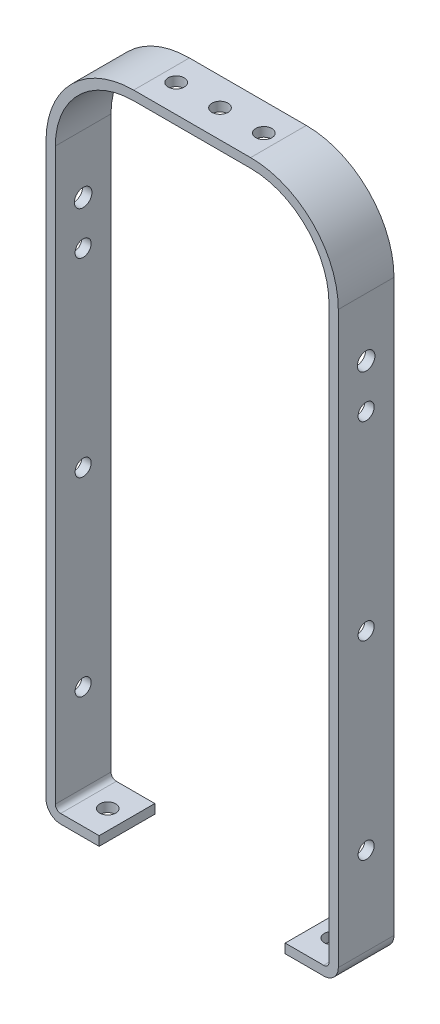
SolidWorks part; units mm, degrees
ref_plane "Front Plane" through (0, 0, 0) normal (0, 0, 1) x (1, 0, 0)
ref_plane "Top Plane" through (0, 0, 0) normal (0, 1, 0) x (1, 0, 0)
ref_plane "Right Plane" through (0, 0, 0) normal (1, 0, 0) x (0, 0, -1)
sketch "Sketch1" plane through (0, 0, 0) normal (0, 0, 1) x (1, 0, 0)
  line L0 (50, 45) -> (50, 240)
  line L1 (0, 0) -> (0, 109.6692) construction
  line L2 (46.825, 240) -> (46.825, 45)
  line L3 (-45, 40) -> (-31.825, 40)
  line L4 (20, 270) -> (-20, 270)
  line L5 (-45, 43.175) -> (-31.825, 43.175)
  line L6 (-20, 266.825) -> (20, 266.825)
  line L7 (-31.825, 43.175) -> (-31.825, 40)
  line L8 (-46.825, 240) -> (-46.825, 45)
  line L9 (-50, 45) -> (-50, 240)
  line L10 (31.825, 43.175) -> (31.825, 40)
  line L11 (45, 43.175) -> (31.825, 43.175)
  line L12 (45, 40) -> (31.825, 40)
  arc A0 (50, 240) -> (20, 270) centre (20, 240) ccw
  arc A1 (20, 266.825) -> (46.825, 240) centre (20, 240) cw
  arc A2 (-20, 266.825) -> (-46.825, 240) centre (-20, 240) ccw
  arc A3 (-50, 240) -> (-20, 270) centre (-20, 240) cw
  arc A4 (-50, 45) -> (-45, 40) centre (-45, 45) ccw
  arc A5 (-46.825, 45) -> (-45, 43.175) centre (-45, 45) ccw
  arc A6 (46.825, 45) -> (45, 43.175) centre (45, 45) cw
  arc A7 (50, 45) -> (45, 40) centre (45, 45) cw
  dimension "D4" = 30
  dimension "D5" = 45
  dimension "D6" = 3.175
  dimension "D7" = 5
  dimension "D1" = 270
  dimension "D2" = 46.825
  dimension "D3" = 40
  dimension "D8" = 15
extrude "Boss-Extrude1" add sketch "Sketch1" along normal mid plane 19.05
sketch "Sketch12" plane through (0, 270, 0) normal (0, 1, 0) x (1, 0, 0)
  line L0 (-20, -9.525) -> (-20, 9.525) construction
  line L1 (20, -9.525) -> (20, 9.525) construction
  circle A0 centre (0, 0) radius 2.75
  circle A1 centre (-15, 0) radius 2.75
  circle A2 centre (15, 0) radius 2.75
  dimension "D1" = 5.5
  dimension "D2" = 5
  dimension "D3" = 5
extrude "Cut-Extrude2" cut sketch "Sketch12" against normal through all
sketch "Sketch13" plane through (50, 0, 0) normal (1, 0, 0) x (0, 0, -1)
  line L0 (0, 0) -> (0, 240) construction
  line L1 (-9.525, 240) -> (9.525, 240) construction
  circle A0 centre (0, 205) radius 2.75
  circle A1 centre (0, 140) radius 2.75
  circle A2 centre (0, 75) radius 2.75
  dimension "D1" = 5.5
  dimension "D4" = 65
  dimension "D3" = 3
extrude "Cut-Extrude3" cut sketch "Sketch13" against normal through all both and the other way through all
sketch "Sketch16" plane through (0, 40, 0) normal (0, -1, 0) x (-1, 0, 0)
  line L0 (38.4125, -9.525) -> (38.4125, 9.525) construction
  line L1 (45, -9.525) -> (31.825, -9.525) construction
  line L2 (45, 9.525) -> (31.825, 9.525) construction
  line L3 (38.4125, 9.525) -> (31.825, 0) construction
  line L4 (31.825, -9.525) -> (31.825, 9.525) construction
  line L5 (31.825, 0) -> (45, 0) construction
  line L6 (45, -9.525) -> (45, 9.525) construction
  line L7 (0, 0) -> (0, -9.525) construction
  line L8 (20, -9.525) -> (-20, -9.525) construction
  circle A0 centre (38.4125, 0) radius 2.75
  circle A1 centre (-38.4125, 0) radius 2.75
  dimension "D1" = 5.5
extrude "Cut-Extrude6" cut sketch "Sketch16" against normal up to next
sketch "Sketch17" plane through (50, 0, 0) normal (1, 0, 0) x (0, 0, -1)
  line L0 (-9.525, 240) -> (9.525, 240) construction
  circle A0 centre (0, 220) radius 3
  point P4 (-2.2021, 225)
  point P5 (0, 0)
  point P8 (0, 0)
  dimension "D1" = 6
  dimension "D2" = 20
extrude "Cut-Extrude7" cut sketch "Sketch17" against normal through all both and the other way through all
